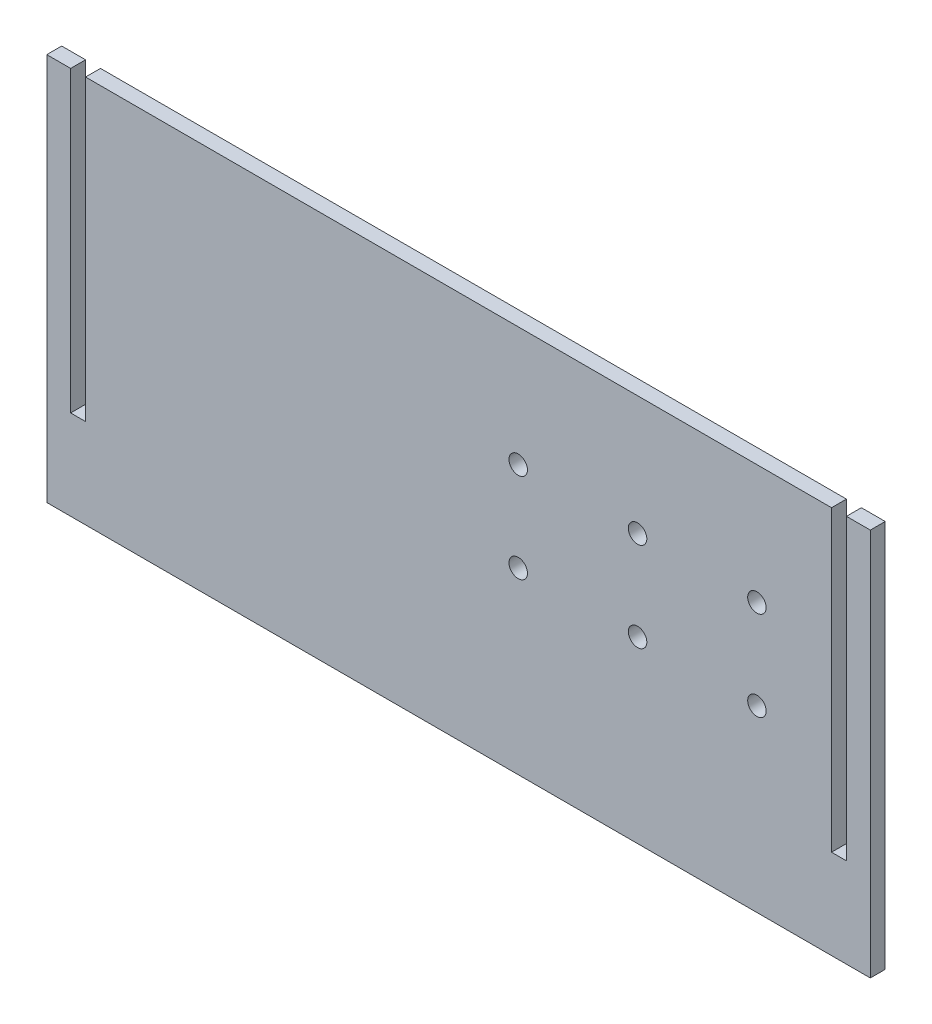
SolidWorks part; units mm, degrees
ref_plane "Alzado" through (0, 0, 0) normal (0, 0, 1) x (1, 0, 0)
ref_plane "Planta" through (0, 0, 0) normal (0, 1, 0) x (1, 0, 0)
ref_plane "Vista lateral" through (0, 0, 0) normal (1, 0, 0) x (0, 0, -1)
sketch "Croquis1" plane through (0, 0, 0) normal (0, 0, 1) x (1, 0, 0)
  line L1 (0, 0) -> (138, 0)
  line L2 (0, 0) -> (0, -65)
  line L3 (0, -65) -> (138, -65)
  line L4 (138, 0) -> (138, -65)
  dimension "D1" = 138
  dimension "D2" = 65
extrude "Saliente-Extruir1" add sketch "Croquis1" along normal blind 2.5
sketch "Croquis2" plane through (0, 0, 2.5) normal (0, 0, 1) x (1, 0, 0)
  line L0 (138, 0) -> (0, 0) construction
  line L1 (4, 0) -> (6.5, 0)
  line L2 (4, 0) -> (4, -50)
  line L3 (4, -50) -> (6.5, -50)
  line L4 (6.5, 0) -> (6.5, -50)
  line L5 (0, 0) -> (0, -65) construction
  line L6 (138, -65) -> (138, 0) construction
  line L7 (131.5, 0.0025) -> (134, 0.0025)
  line L8 (131.5, 0.0025) -> (131.5, -49.9975)
  line L9 (131.5, -49.9975) -> (134, -49.9975)
  line L10 (134, 0.0025) -> (134, -49.9975)
  dimension "D1" = 50
  dimension "D2" = 2.5
  dimension "D3" = 4
  dimension "D4" = 50
  dimension "D5" = 2.5
  dimension "D6" = 4
extrude "Cortar-Extruir1" cut sketch "Croquis2" against normal blind 2.5
sketch "Croquis3" plane through (0, 0, 2.5) normal (0, 0, 1) x (1, 0, 0)
  line L0 (0, -65) -> (138, -65) construction
  line L2 (134, -49.9975) -> (134, 0) construction
  circle A0 centre (119, -35) radius 1.55
  circle A1 centre (119, -20) radius 1.55
  circle A2 centre (99, -35) radius 1.55
  circle A3 centre (99, -20) radius 1.55
  circle A4 centre (79, -35) radius 1.55
  circle A5 centre (79, -20) radius 1.55
  dimension "D3" = 3.1
  dimension "D1" = 30
  dimension "D2" = 15
  dimension "D4" = 15
  dimension "D5" = 20
  dimension "D6" = 20
extrude "Cortar-Extruir2" cut sketch "Croquis3" against normal through all
